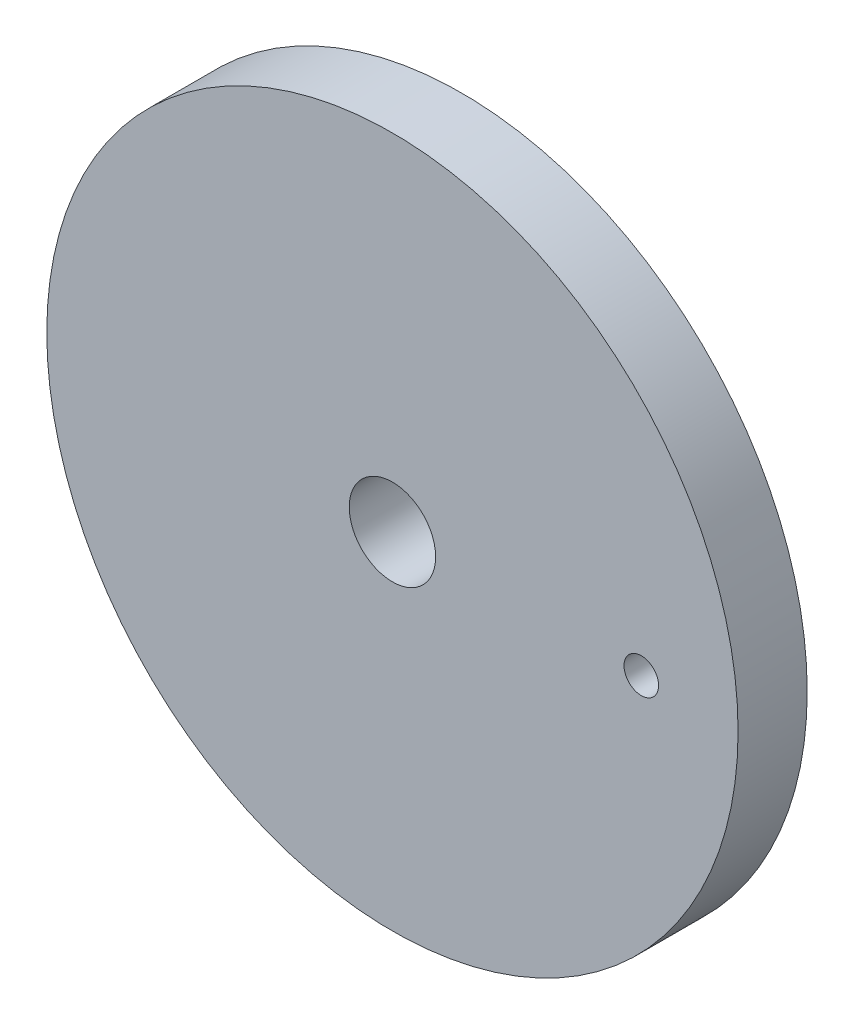
SolidWorks part; units mm, degrees
ref_plane "前视基准面" through (0, 0, 0) normal (0, 0, 1) x (1, 0, 0)
ref_plane "上视基准面" through (0, 0, 0) normal (0, 1, 0) x (1, 0, 0)
ref_plane "右视基准面" through (0, 0, 0) normal (1, 0, 0) x (0, 0, -1)
sketch "草图1" plane through (0, 0, 0) normal (0, 0, 1) x (1, 0, 0)
  circle A0 centre (0, 0) radius 6.25
  circle A4 centre (0, 0) radius 50
  circle A6 centre (36, 0) radius 2.5
  dimension "D1" = 100
  dimension "D2" = 36
extrude "凸台-拉伸1" add sketch "草图1" along normal blind 10
